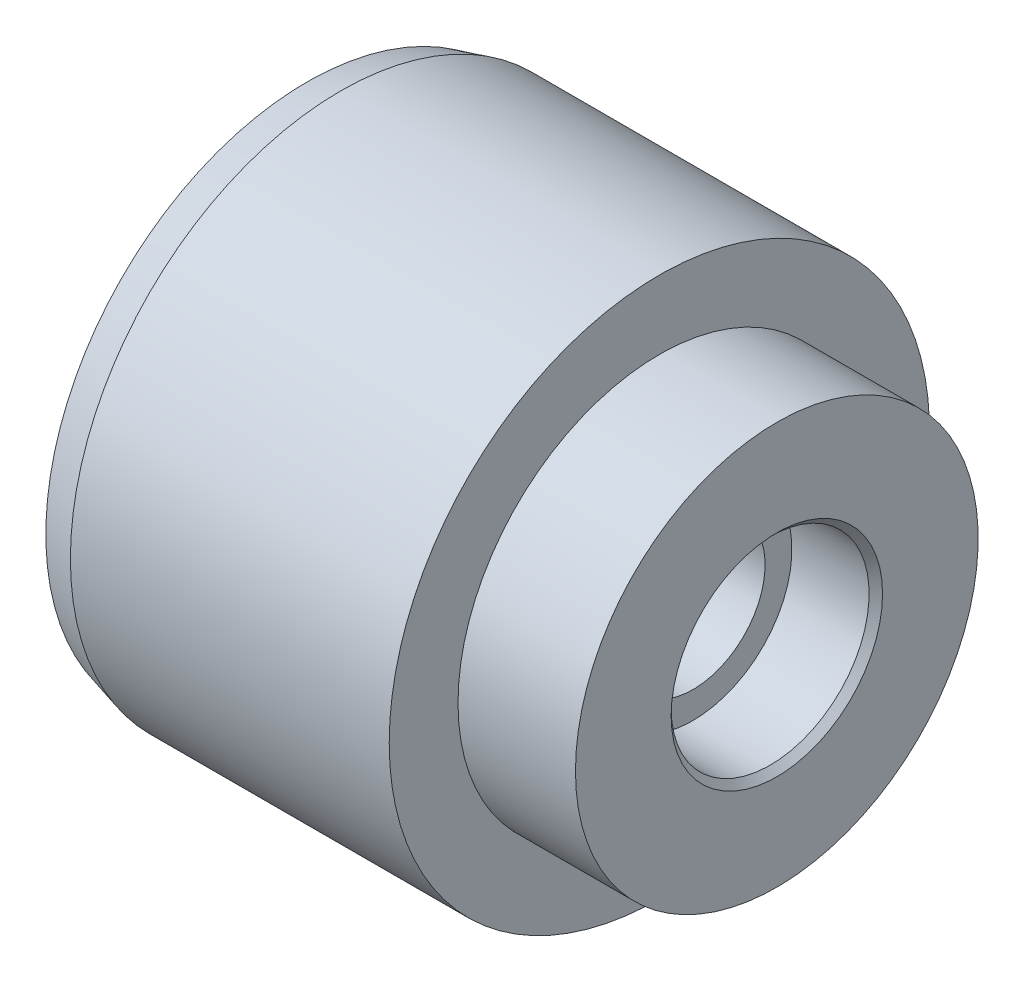
SolidWorks part; units mm, degrees
material "ABS"
ref_plane "Спереди" through (0, 0, 0) normal (0, 0, 1) x (1, 0, 0)
ref_plane "Сверху" through (0, 0, 0) normal (0, 1, 0) x (1, 0, 0)
ref_plane "Справа" through (0, 0, 0) normal (1, 0, 0) x (0, 0, -1)
sketch "Эскиз1" plane through (0, 0, 0) normal (0, 0, 1) x (1, 0, 0)
  line L0 (-5.8819, 0) -> (8.2434, 0) construction
  line L1 (14, 2.95) -> (11.5, 2.95)
  line L2 (0, 0) -> (11.5, 0)
  line L3 (0, 0) -> (0, 8.05)
  line L4 (0, 8.05) -> (10.5, 8.05)
  line L5 (14, 2.95) -> (14, 6)
  line L6 (11.5, 2.95) -> (11.5, 0)
  line L7 (10.5, 8.05) -> (10.5, 6)
  line L8 (10.5, 6) -> (14, 6)
  dimension "D1" = 16.1
  dimension "D2" = 5.9
  dimension "D3" = 2.5
  dimension "D4" = 14
  dimension "D5" = 12
  dimension "D6" = 3.5
revolve "Повернуть1" add sketch "Эскиз1" angle 360 about L0
chamfer "Фаска1" distance 1 angle 15 1 edges at (0, 0, 8.05)
chamfer "Фаска2" distance 0.2 angle 45 1 edges at (14, 0, 2.95)
hole_wizard "Отверстие с зазором 1" positions "Эскиз3" profile "Эскиз2" hole size "M4" standard "DIN" end condition through all
sketch "Эскиз3" plane through (0, 0, 0) normal (-1, 0, 0) x (0, 0, 1)
  point P0 (0, 0)
sketch "Эскиз2" plane through (0, 0, 0) normal (0, 1, 0) x (0, 0, 1)
  line L0 (0, 0) -> (0, 14)
  line L1 (0, 14) -> (2.15, 14)
  line L2 (2.15, 14) -> (2.15, 0)
  line L5 (2.15, 0) -> (0, 0)
  line L11 (0, -6.35) -> (0, 107.95) construction
  dimension "Диаметр сквозного отверстия" = 4.3
  dimension "Глубина сквозного отверстия" = 14
